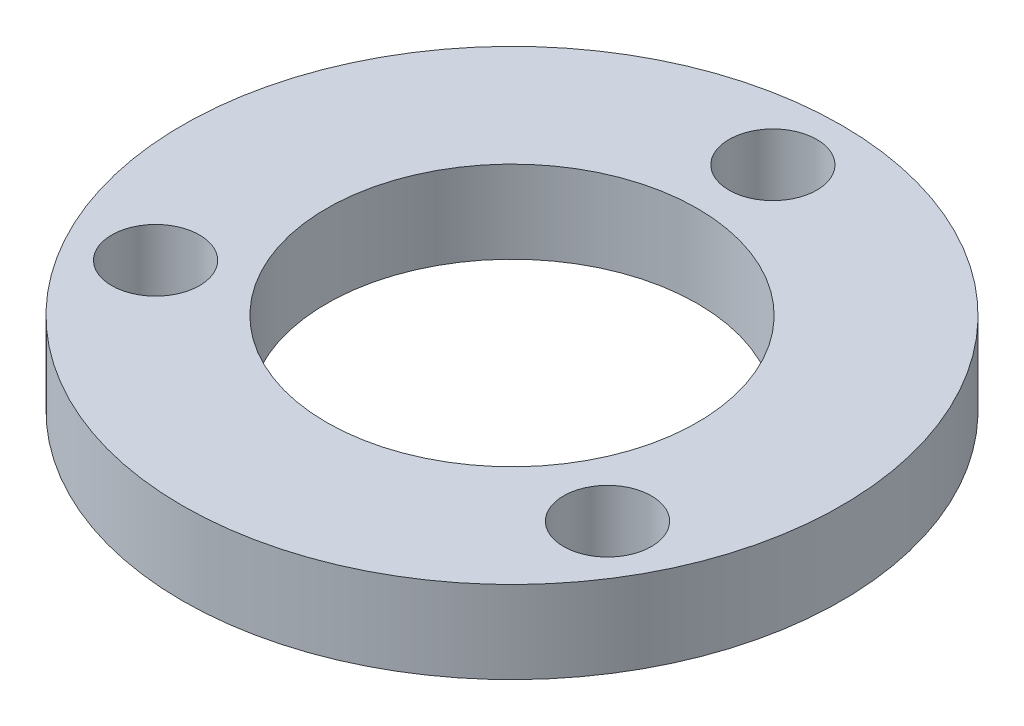
SolidWorks part; units mm, degrees
material "ABS"
ref_plane "前视基准面" through (0, 0, 0) normal (0, 0, 1) x (1, 0, 0)
ref_plane "上视基准面" through (0, 0, 0) normal (0, 1, 0) x (1, 0, 0)
ref_plane "右视基准面" through (0, 0, 0) normal (1, 0, 0) x (0, 0, -1)
sketch "草图1" plane through (0, 0, 0) normal (0, 1, 0) x (1, 0, 0)
  circle A0 centre (0, 0) radius 9.5 construction
  circle A1 centre (0, 9.5) radius 1.6
  circle A2 centre (8.2272, -4.75) radius 1.6
  circle A3 centre (-8.2272, -4.75) radius 1.6
  circle A4 centre (0, 0) radius 12
  circle A5 centre (0, 0) radius 6.75
  point P12 (0, 0)
  dimension "D1" = 19
  dimension "D2" = 3.2
  dimension "D4" = 24
  dimension "D5" = 13.5
  dimension "D3" = 3
extrude "凸台-拉伸1" add sketch "草图1" along normal blind 3
